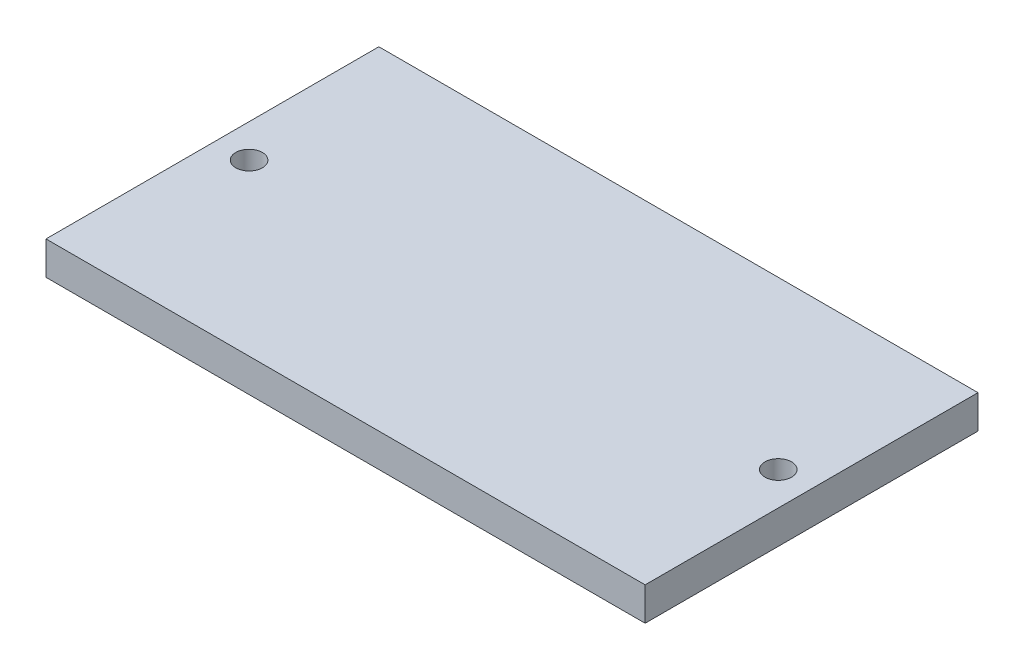
SolidWorks part; units mm, degrees
ref_plane "Front Plane" through (0, 0, 0) normal (0, 0, 1) x (1, 0, 0)
ref_plane "Top Plane" through (0, 0, 0) normal (0, 1, 0) x (1, 0, 0)
ref_plane "Right Plane" through (0, 0, 0) normal (1, 0, 0) x (0, 0, -1)
sketch "草图1" plane through (0, 0, 0) normal (0, 1, 0) x (1, 0, 0)
  line L1 (45, -25) -> (-45, -25)
  line L2 (45, -25) -> (45, 25)
  line L3 (45, 25) -> (-45, 25)
  line L4 (-45, -25) -> (-45, 25)
  line L5 (45, -25) -> (-45, 25) construction
  line L6 (45, 25) -> (-45, -25) construction
  circle A0 centre (-39.9969, 0.5) radius 2
  circle A1 centre (40, 0) radius 2
  point P0 (0, 0)
  point P10 (0, 0)
  dimension "D3" = 4
  dimension "D4" = 4
  dimension "D7" = 25.5
  dimension "D1" = 50
  dimension "D2" = 90
  dimension "D5" = 40
  dimension "D6" = 40
extrude "凸台-拉伸1" add sketch "草图1" along normal blind 5
